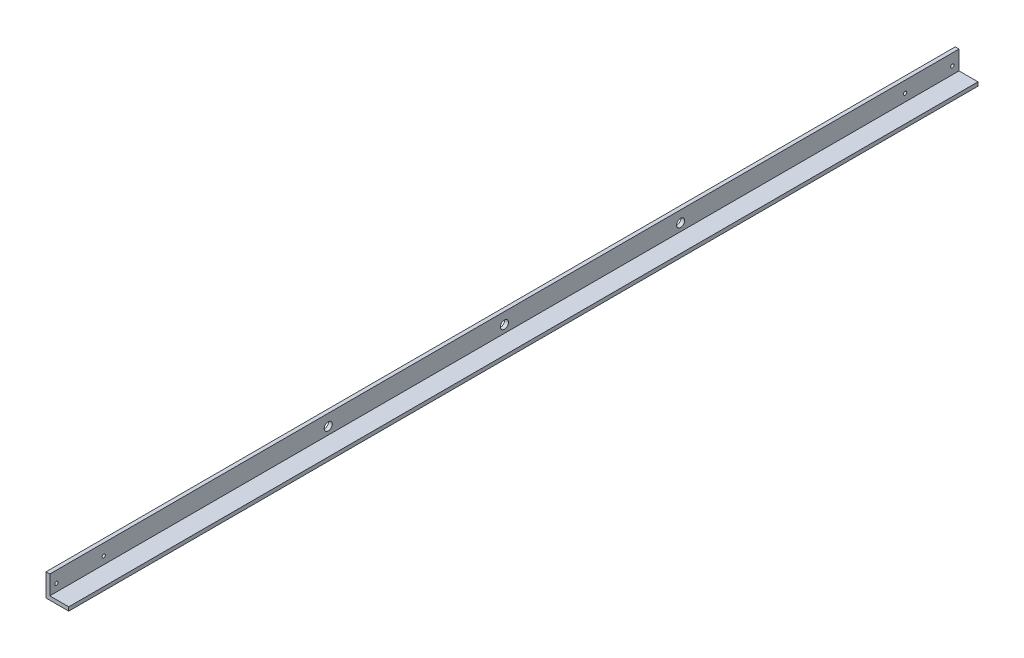
SolidWorks part; units mm, degrees
ref_plane "Front Plane" through (0, 0, 0) normal (0, 0, 1) x (1, 0, 0)
ref_plane "Top Plane" through (0, 0, 0) normal (0, 1, 0) x (1, 0, 0)
ref_plane "Right Plane" through (0, 0, 0) normal (1, 0, 0) x (0, 0, -1)
sketch "Sketch1" plane through (0, 0, 0) normal (0, 0, 1) x (1, 0, 0)
  line L0 (0, 0) -> (19.05, 0)
  line L1 (19.05, 0) -> (19.05, 3.175)
  line L2 (19.05, 3.175) -> (3.175, 3.175)
  line L3 (3.175, 3.175) -> (3.175, 19.05)
  line L4 (3.175, 19.05) -> (0, 19.05)
  line L5 (0, 19.05) -> (0, 0)
  dimension "D1" = 19.05
  dimension "D3" = 3.175
  dimension "D4" = 19.05
extrude "Boss-Extrude1" add sketch "Sketch1" along normal blind 762
hole_wizard "#35 (0.11) Diameter Hole1" positions "3DSketch1" profile "Sketch2" hole size "#35" standard "Ansi Inch" end condition through all
sketch3d "3DSketch1"
  line L5 (0, 19.05, 0) -> (0, 0, 0) construction
  line L7 (0, 9.525, 0) -> (0, 9.525, 762) construction
  line L9 (0, 0, 762) -> (0, 0, 0) construction
  line L10 (0, 19.05, 762) -> (0, 0, 762) construction
  line L11 (0, 9.525, 381) -> (0, -61.5173, 381) construction
  point P39 (0, 9.525, 5.588)
  point P42 (0, 9.525, 45.212)
  point P48 (0, 9.525, 716.787)
  point P50 (0, 9.525, 756.412)
  dimension "D1" = 9.525
  dimension "D3" = 39.624
  dimension "D2" = 375.412
  dimension "D4" = 39.625
  dimension "D5" = 750.824
sketch "Sketch2" plane through (0, 9.525, 5.588) normal (0, 1, 0) x (0, 0, 1)
  line L0 (0, 0) -> (0, 19.05)
  line L1 (0, 19.05) -> (1.397, 19.05)
  line L2 (1.397, 19.05) -> (1.397, 0)
  line L5 (1.397, 0) -> (0, 0)
  line L11 (0, -6.35) -> (0, 107.95) construction
  dimension "Thru Hole Dia." = 2.794
  dimension "Thru Hole Depth" = 19.05
hole_wizard "17/64 (0.26563) Diameter Hole1" positions "3DSketch2" profile "Sketch3" hole size "17/64" standard "Ansi Inch"
sketch3d "3DSketch2"
  line L0 (0, 9.525, 5.588) -> (0, 9.525, 756.412) construction
  line L1 (3.175, 9.525, 5.588) -> (0, 9.525, 5.588) construction
  line L2 (3.175, 9.525, 756.412) -> (0, 9.525, 756.412) construction
  point P8 (0, 9.525, 381)
  point P11 (0, 9.525, 233.3625)
  point P13 (0, 9.525, 528.6375)
  point P14 (0, 9.525, 381)
  dimension "D1" = 295.275
  dimension "D2" = 147.6375
sketch "Sketch3" plane through (0, 9.525, 233.3625) normal (0, 1, 0) x (0, 0, 1)
  line L0 (0, 0) -> (0, 12.027)
  line L1 (0, 12.027) -> (3.3735, 10)
  line L2 (3.3735, 10) -> (3.3735, 0)
  line L5 (3.3735, 0) -> (0, 0)
  line L10 (0, 12.027) -> (-3.3735, 10) construction
  line L11 (0, -6.35) -> (0, 107.95) construction
  dimension "Hole Dia." = 6.747
  dimension "Hole Depth" = 10
  dimension "Drill Angle" = 118
equation "\"D2@3DSketch2\" = \"D1@3DSketch2\"/2"
equation "\"D2@3DSketch1\" = \"D5@3DSketch1\"/2"
